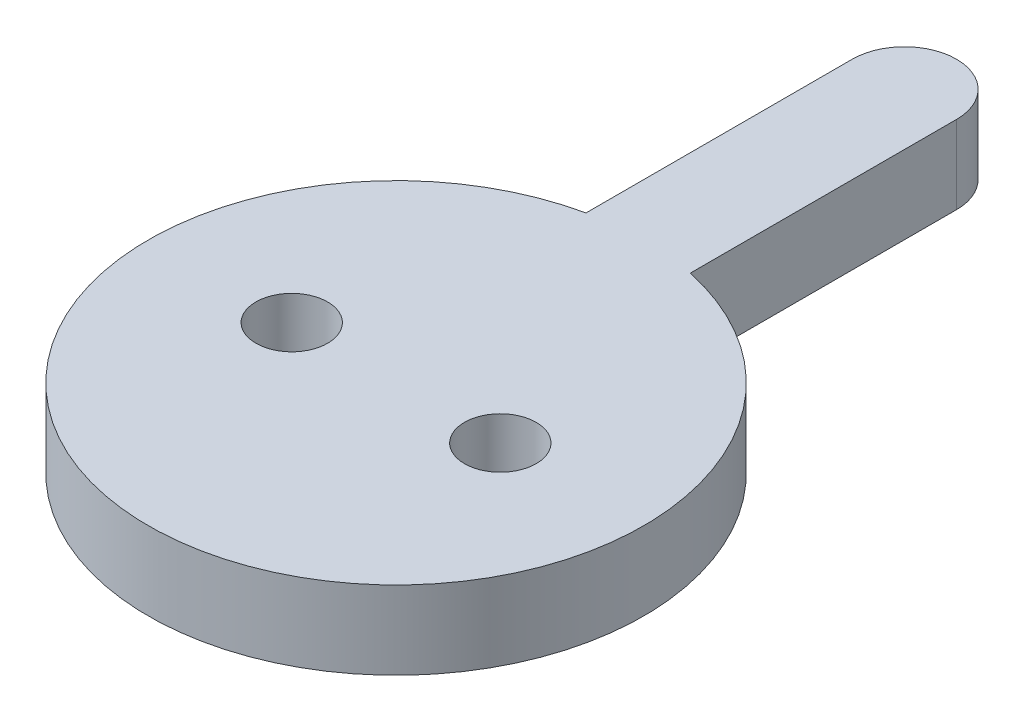
SolidWorks part; units mm, degrees
ref_plane "Front Plane" through (0, 0, 0) normal (0, 0, 1) x (1, 0, 0)
ref_plane "Top Plane" through (0, 0, 0) normal (0, 1, 0) x (1, 0, 0)
ref_plane "Right Plane" through (0, 0, 0) normal (1, 0, 0) x (0, 0, -1)
sketch "Sketch1" plane through (0, 0, 0) normal (0, 1, 0) x (1, 0, 0)
  line L0 (0, 19) -> (0, 39)
  line L1 (0, 39) -> (-4, 39)
  line L2 (0, 39) -> (4, 39)
  line L3 (-4, 39) -> (-4, 18.5742)
  line L4 (4, 39) -> (4, 18.5742)
  circle A0 centre (0, 0) radius 19
  arc A1 (-4, 39) -> (4, 39) centre (0, 39) cw
  dimension "D1" = 20
  dimension "D2" = 38
  dimension "D3" = 4
  dimension "D4" = 4
extrude "Boss-Extrude1" add sketch "Sketch1" along normal blind 6 contours A1 L1 L2 | A0 L0 L1 L3 | A0 L4 L2 L0 | A0
sketch "Sketch3" plane through (0, 0, 0) normal (0, -1, 0) x (1, 0, 0)
  circle A0 centre (0, 0) radius 14.86
extrude "Boss-Extrude2" add sketch "Sketch3" along normal blind 2
sketch "Sketch2" plane through (0, 6, 0) normal (0, 1, 0) x (1, 0, 0)
  circle A0 centre (8, 0) radius 2.75
  circle A1 centre (-8, 0) radius 2.75
  dimension "D1" = 8
  dimension "D2" = 8
extrude "Cut-Extrude1" cut sketch "Sketch2" against normal blind 10
sketch "Sketch4" plane through (0, -2, 0) normal (0, -1, 0) x (1, 0, 0)
  line L1 (0, 11.547) -> (-10, 5.7735)
  line L2 (-10, 5.7735) -> (-10, -5.7735)
  line L3 (-10, -5.7735) -> (0, -11.547)
  line L4 (0, -11.547) -> (10, -5.7735)
  line L5 (10, -5.7735) -> (10, 5.7735)
  line L6 (10, 5.7735) -> (0, 11.547)
  circle A1 centre (0, 0) radius 10 construction
  dimension "D1" = 20
